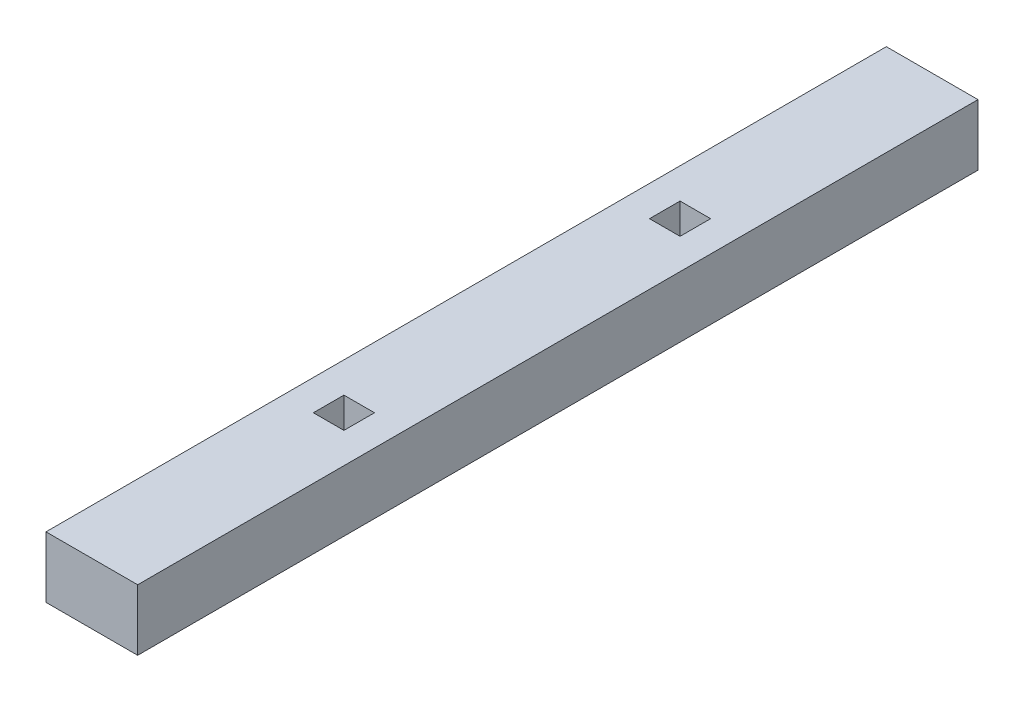
SolidWorks part; units mm, degrees
ref_plane "Front Plane" through (0, 0, 0) normal (0, 0, 1) x (1, 0, 0)
ref_plane "Top Plane" through (0, 0, 0) normal (0, 1, 0) x (1, 0, 0)
ref_plane "Right Plane" through (0, 0, 0) normal (1, 0, 0) x (0, 0, -1)
sketch "Sketch1" plane through (0, 0, 0) normal (0, 1, 0) x (1, 0, 0)
  line L0 (0, 132.5) -> (0, -142.5) construction
  line L1 (-15, 132.5) -> (15, 132.5)
  line L2 (-15, 132.5) -> (-15, -142.5)
  line L3 (-15, -142.5) -> (15, -142.5)
  line L4 (15, 132.5) -> (15, -142.5)
  line L5 (-5, 55) -> (5, 55)
  line L6 (-5, 55) -> (-5, 45)
  line L7 (-5, 45) -> (5, 45)
  line L8 (5, 55) -> (5, 45)
  line L9 (15, -5) -> (-15, -5) construction
  line L10 (-5, -65) -> (-5, -55)
  line L11 (-5, -55) -> (5, -55)
  line L12 (5, -65) -> (5, -55)
  line L13 (-5, -65) -> (5, -65)
  point P9 (0, 55)
  point P10 (0, 132.5)
  dimension "D3" = 10
  dimension "D5" = 100
  dimension "D4" = 10
  dimension "D1" = 30
  dimension "D2" = 275
extrude "Boss-Extrude1" add sketch "Sketch1" along normal blind 20
